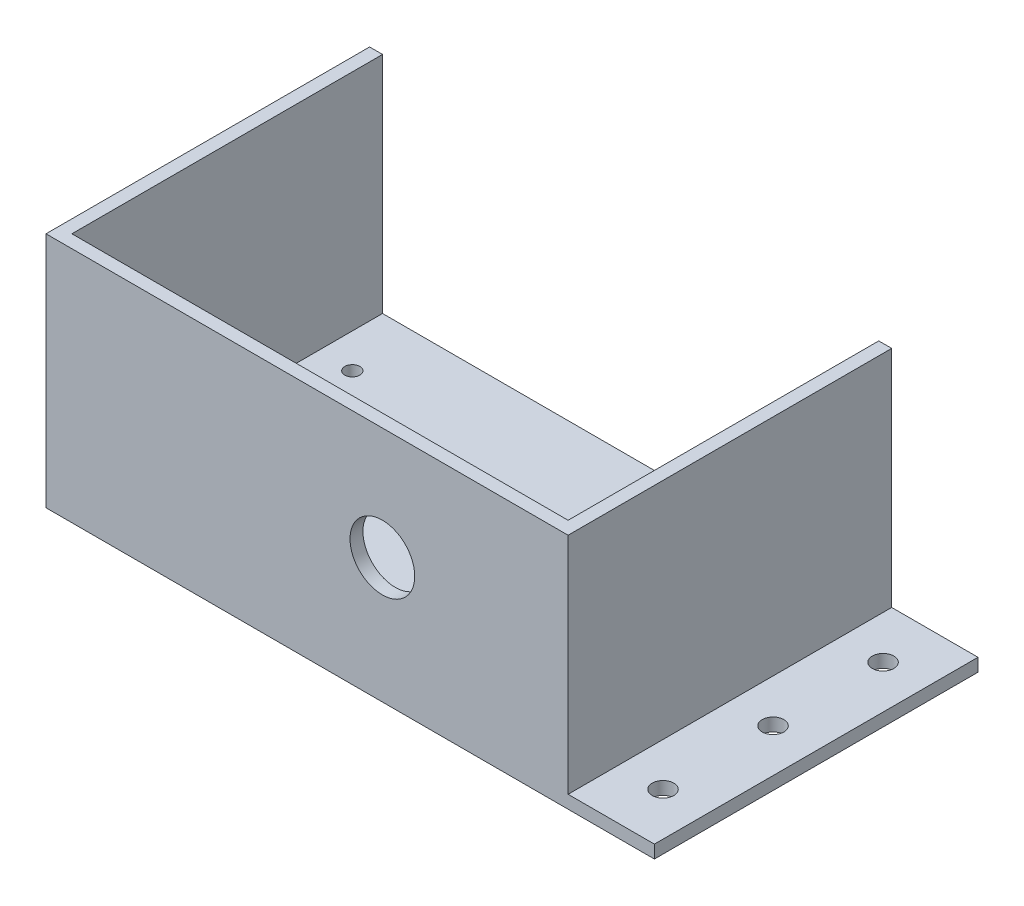
SolidWorks part; units mm, degrees
ref_plane "Front Plane" through (0, 0, 0) normal (0, 0, 1) x (1, 0, 0)
ref_plane "Top Plane" through (0, 0, 0) normal (0, 1, 0) x (1, 0, 0)
ref_plane "Right Plane" through (0, 0, 0) normal (1, 0, 0) x (0, 0, -1)
sketch "Sketch1" plane through (0, 0, 0) normal (0, 1, 0) x (1, 0, 0)
  line L1 (0, 0) -> (121, 0)
  line L2 (0, 0) -> (0, 75)
  line L3 (0, 75) -> (121, 75)
  line L4 (121, 0) -> (121, 75)
  dimension "D1" = 121
  dimension "D2" = 75
extrude "Boss-Extrude1" add sketch "Sketch1" along normal blind 58
sketch "Sketch2" plane through (0, 0, -75) normal (0, 0, -1) x (-1, 0, 0)
  line L0 (-121, 0) -> (0, 0) construction
  line L1 (-3, 3) -> (-118, 3)
  line L2 (-3, 3) -> (-3, 55)
  line L3 (-3, 55) -> (-118, 55)
  line L4 (-118, 3) -> (-118, 55)
  line L5 (0, 58) -> (0, 0) construction
  line L6 (-121, 58) -> (-121, 0) construction
  dimension "D1" = 52
  dimension "D2" = 3
  dimension "D3" = 3
  dimension "D4" = 3
extrude "Cut-Extrude1" cut sketch "Sketch2" against normal blind 72
sketch "Sketch4" plane through (0, 58, 0) normal (0, 1, 0) x (1, 0, 0)
  text T0 "IMAGINEER" height 10
  point P1 (10.2539, 54.8174)
  point P2 (13.2882, 55.256)
  point P3 (0, 0)
  point P4 (0, 0)
extrude "Boss-Extrude2" add sketch "Sketch4" along normal blind 1.5
sketch "Sketch5" plane through (0, 58, 0) normal (0, 1, 0) x (-1, 0, 0)
  line L12 (-60.5, 72.992) -> (-60.5, -137.1284) construction
  line L13 (-84.629, -12.2531) -> (-42.629, -12.2531)
  line L14 (-42.629, -12.2531) -> (-36.329, -18.1531)
  line L15 (-36.329, -18.1531) -> (-36.329, -34.1531)
  line L16 (-36.329, -34.1531) -> (-42.629, -40.0531)
  line L17 (-84.629, -12.2531) -> (-84.629, -40.0531)
  line L18 (-84.629, -40.0531) -> (-42.629, -40.0531)
  circle A4 centre (-60.4781, -46.043) radius 1.4898
  circle A5 centre (-60.5065, -6.2504) radius 1.5
  point P0 (0, 0)
  point P2 (0, 0)
  point P7 (0, 0)
  dimension "D1" = 60.5
extrude "Cut-Extrude2" cut sketch "Sketch5" against normal blind 5
sketch "Sketch6" plane through (121, 0, 0) normal (1, 0, 0) x (0, 0, -1)
  line L0 (75, 58) -> (75, 0) construction
  line L1 (0, 0) -> (75, 0)
  line L2 (0, 0) -> (0, 3)
  line L3 (0, 3) -> (75, 3)
  line L4 (75, 0) -> (75, 3)
  dimension "D1" = 3
extrude "Boss-Extrude3" add sketch "Sketch6" along normal blind 20
sketch "Sketch7" plane through (0, 3, 0) normal (0, 1, 0) x (1, 0, 0)
  line L0 (141, 75) -> (141, 0) construction
  line L1 (141, 75) -> (121, 75) construction
  line L2 (141, 0) -> (121, 0) construction
  circle A0 centre (131, 63) radius 2.5
  circle A1 centre (131, 37.5) radius 2.5
  circle A2 centre (131, 12) radius 2.5
  point P12 (0, 0)
  dimension "D1" = 5
  dimension "D2" = 10
  dimension "D3" = 12
  dimension "D4" = 12
  dimension "D5" = 25.5
extrude "Cut-Extrude3" cut sketch "Sketch7" against normal blind 20
sketch "Sketch8" plane through (0, 0, 0) normal (0, 0, 1) x (1, 0, 0)
  line L0 (0, 0) -> (141, 0) construction
  circle A1 centre (77.9556, 29) radius 7.5
  dimension "D1" = 29
extrude "Cut-Extrude4" cut sketch "Sketch8" against normal blind 5
sketch "Sketch9" plane through (0, 0, 0) normal (0, -1, 0) x (1, 0, 0)
  line L0 (141, -75) -> (0, -75) construction
  line L1 (0, -75) -> (0, 0) construction
  line L2 (141, 0) -> (141, -75) construction
  circle A0 centre (11, -60) radius 1.75
  circle A1 centre (110, -60) radius 1.75
  point P6 (0, 0)
  dimension "D1" = 3.5
  dimension "D2" = 15
  dimension "D3" = 11
  dimension "D4" = 31
extrude "Cut-Extrude5" cut sketch "Sketch9" against normal blind 5
sketch "Sketch10" plane through (0, 0, 0) normal (0, 0, 1) x (1, 0, 0)
  line L0 (0, 58) -> (0, 0) construction
  line L1 (0, 55) -> (121, 55)
  line L2 (0, 55) -> (0, 65.055)
  line L3 (0, 65.055) -> (121, 65.055)
  line L4 (121, 55) -> (121, 65.055)
  dimension "D1" = 3
extrude "Cut-Extrude6" cut sketch "Sketch10" against normal through all
